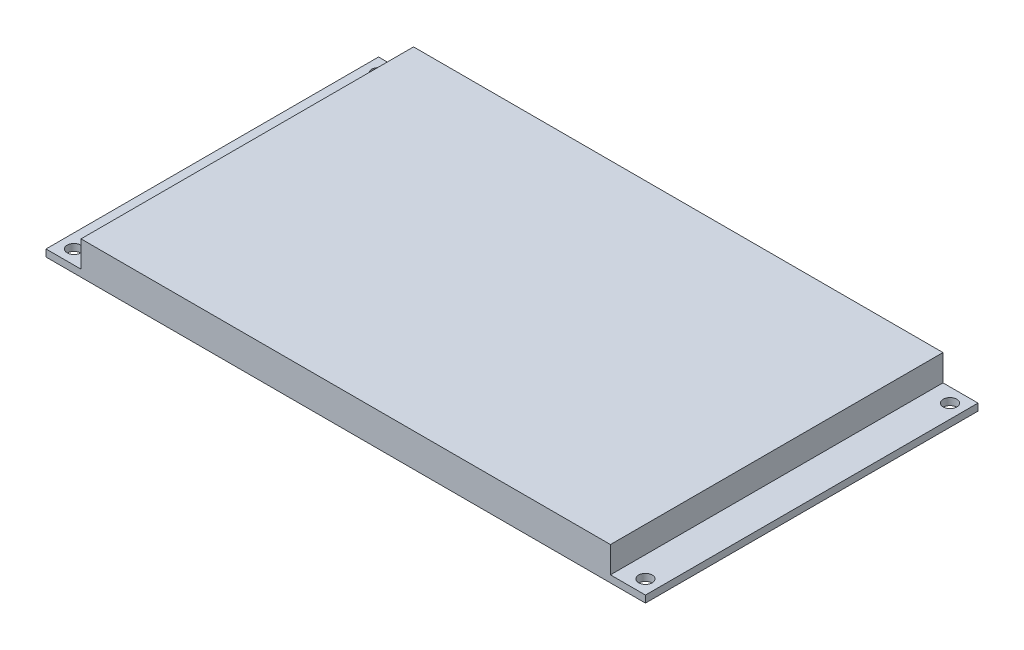
SolidWorks part; units mm, degrees
ref_plane "前视基准面" through (0, 0, 0) normal (0, 0, 1) x (1, 0, 0)
ref_plane "上视基准面" through (0, 0, 0) normal (0, 1, 0) x (1, 0, 0)
ref_plane "右视基准面" through (0, 0, 0) normal (1, 0, 0) x (0, 0, -1)
sketch "草图1" plane through (0, 0, 0) normal (0, 1, 0) x (1, 0, 0)
  line L1 (0, 0) -> (137, 0)
  line L2 (0, 0) -> (0, -76)
  line L3 (0, -76) -> (137, -76)
  line L4 (137, 0) -> (137, -76)
  dimension "D1" = 137
  dimension "D2" = 76
extrude "凸台-拉伸1" add sketch "草图1" along normal blind 1.6
sketch "草图2" plane through (0, 1.6, 0) normal (0, 1, 0) x (1, 0, 0)
  line L0 (137, 0) -> (0, 0) construction
  line L1 (8, 0) -> (129, 0)
  line L2 (8, 0) -> (8, -76)
  line L3 (8, -76) -> (129, -76)
  line L4 (129, 0) -> (129, -76)
  line L5 (8, -38) -> (0, -38) construction
  line L8 (129, -38) -> (137, -38) construction
  line L11 (137, -76) -> (137, 0) construction
  dimension "D1" = 121
  dimension "D2" = 76
  dimension "D3" = 0
extrude "凸台-拉伸2" add sketch "草图2" along normal blind 6
sketch "草图3" plane through (0, 1.6, 0) normal (0, 1, 0) x (1, 0, 0)
  line L0 (3.2, -3.2) -> (3.2, 0) construction
  line L2 (3.2, -3.2) -> (0, -3.2) construction
  line L3 (0, 0) -> (0, -76) construction
  line L4 (8, 0) -> (0, 0) construction
  line L5 (133.8, -72.8) -> (137, -72.8) construction
  line L6 (137, -76) -> (137, 0) construction
  line L7 (133.8, -72.8) -> (133.8, -76) construction
  line L8 (129, -76) -> (137, -76) construction
  circle A0 centre (3.2, -3.2) radius 1.55
  circle A1 centre (3.2, -72.8) radius 1.55
  circle A2 centre (133.8, -3.2) radius 1.55
  circle A3 centre (133.8, -72.8) radius 1.55
  dimension "D1" = 3.1
  dimension "D2" = 3.2
  dimension "D3" = 3.2
extrude "切除-拉伸1" cut sketch "草图3" against normal blind 5.6
